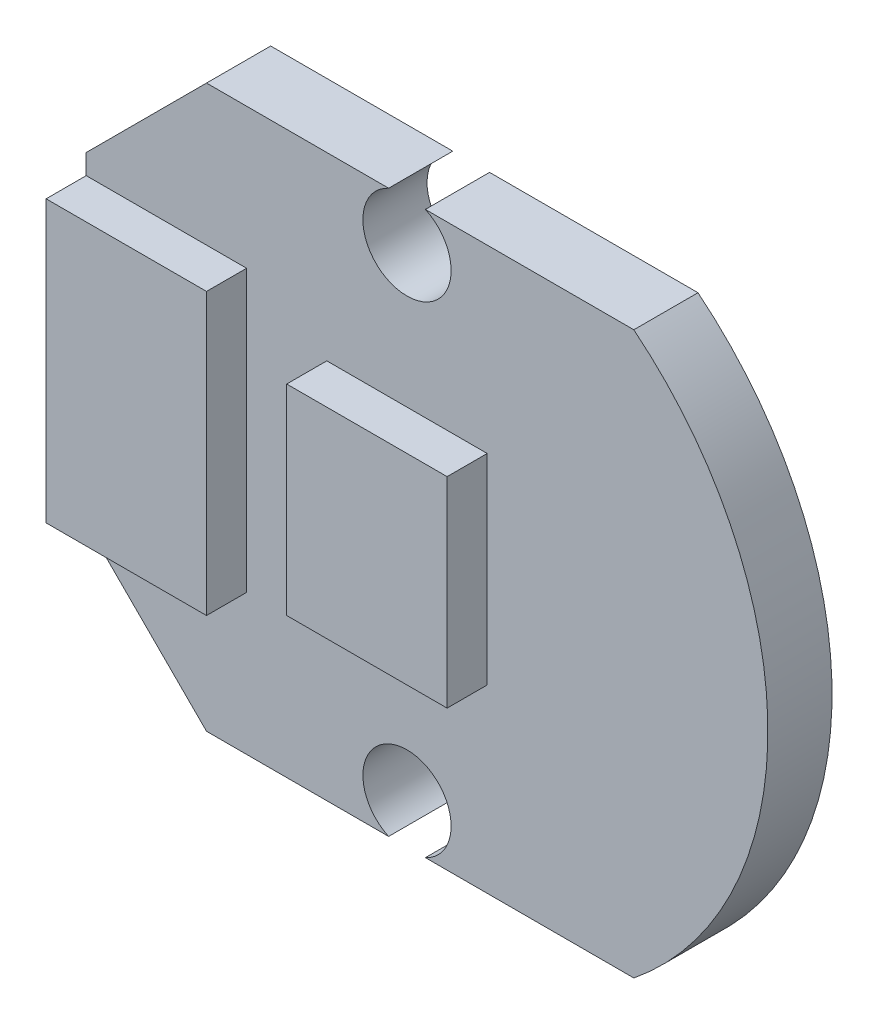
SolidWorks part; units mm, degrees
ref_plane "Alzado" through (0, 0, 0) normal (0, 0, 1) x (1, 0, 0)
ref_plane "Planta" through (0, 0, 0) normal (0, 1, 0) x (1, 0, 0)
ref_plane "Vista lateral" through (0, 0, 0) normal (1, 0, 0) x (0, 0, -1)
sketch "Croquis1" plane through (0, 0, 0) normal (0, 0, 1) x (1, 0, 0)
  line L0 (5.6569, 7) -> (-5, 7)
  line L1 (-5, 7) -> (-8, 4)
  line L2 (-8, 4) -> (-8, -4)
  line L3 (-8, -4) -> (-5, -7)
  line L4 (-5, -7) -> (5.6569, -7)
  line L5 (0, 0) -> (-50000, 0) construction
  line L6 (0, 0) -> (0, 50000) construction
  circle A0 centre (0, 0) radius 9 construction
  arc A1 (5.6569, 7) -> (5.6569, -7) centre (0, 0) cw
  dimension "D1" = 18
  dimension "D2" = 8
  dimension "D3" = 7
  dimension "6" = 7
  dimension "D4" = 45
  dimension "D5" = 45
  dimension "D6" = 3
extrude "Saliente-Extruir1" add sketch "Croquis1" along normal blind 1.6
sketch "Croquis2" plane through (0, 0, 1.6) normal (0, 0, 1) x (1, 0, 0)
  line L0 (0, -200000) -> (0, 250000) construction
  line L1 (200000, 0) -> (-250000, 0) construction
  line L2 (0, 0) -> (50000, 0) construction
  circle A0 centre (0, 6) radius 1.1
  circle A1 centre (0, -6) radius 1.1
  dimension "D1" = 2.2
  dimension "D2" = 6
extrude "Cortar-Extruir2" cut sketch "Croquis2" against normal through all
sketch "Croquis3" plane through (0, 0, 1.6) normal (0, 0, 1) x (1, 0, 0)
  line L0 (200000, 0) -> (-250000, 0) construction
  line L1 (-2, 2.5) -> (2, 2.5)
  line L2 (-2, 2.5) -> (-2, -2.5)
  line L3 (-2, -2.5) -> (2, -2.5)
  line L4 (2, 2.5) -> (2, -2.5)
  line L5 (-2, 2.5) -> (2, -2.5) construction
  line L6 (-2, -2.5) -> (2, 2.5) construction
  line L7 (-4, -3.5) -> (-8, -3.5)
  line L8 (-4, -3.5) -> (-4, 3.5)
  line L9 (-4, 3.5) -> (-8, 3.5)
  line L10 (-8, -3.5) -> (-8, 3.5)
  line L11 (-4, -3.5) -> (-8, 3.5) construction
  line L12 (-4, 3.5) -> (-8, -3.5) construction
  line L13 (-8, 4) -> (-8, -4) construction
  point P0 (0, 0)
  point P6 (-6, 0)
  dimension "D1" = 4
  dimension "D2" = 5
  dimension "D3" = 4
  dimension "D4" = 7
extrude "Saliente-Extruir2" add sketch "Croquis3" along normal blind 1
